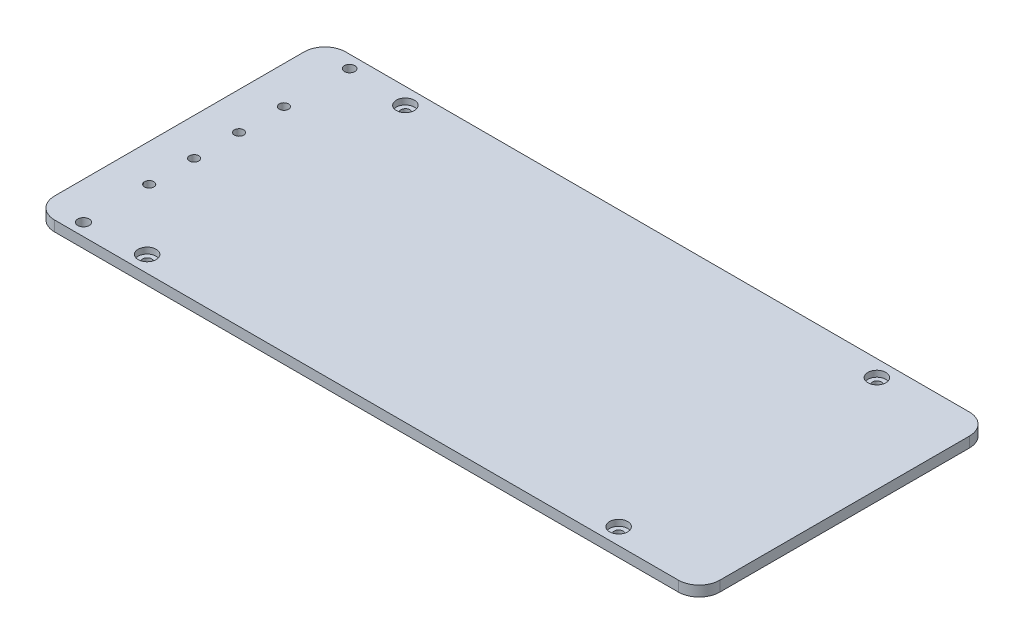
SolidWorks part; units mm, degrees
material "1060 Alloy"
ref_plane "Front Plane" through (0, 0, 0) normal (0, 0, 1) x (1, 0, 0)
ref_plane "Top Plane" through (0, 0, 0) normal (0, 1, 0) x (1, 0, 0)
ref_plane "Right Plane" through (0, 0, 0) normal (1, 0, 0) x (0, 0, -1)
sketch "Sketch1" plane through (0, 0, 0) normal (0, 1, 0) x (1, 0, 0)
  line L1 (-203.2, 88.9) -> (203.2, 88.9)
  line L2 (-203.2, 88.9) -> (-203.2, -88.9)
  line L3 (-203.2, -88.9) -> (203.2, -88.9)
  line L4 (203.2, 88.9) -> (203.2, -88.9)
  line L5 (-203.2, 88.9) -> (203.2, -88.9) construction
  line L6 (-203.2, -88.9) -> (203.2, 88.9) construction
  point P0 (0, 0)
  dimension "D1" = 406.4
  dimension "D2" = 177.8
extrude "Boss-Extrude1" add sketch "Sketch1" along normal blind 6.35 contours L4 L3 L2 L1
fillet "Fillet1" radius 12.7 4 edges at (-203.2, 3.175, -88.9) (-203.2, 3.175, 88.9) (203.2, 3.175, -88.9) (203.2, 3.175, 88.9)
sketch "Sketch2" plane through (0, 6.35, 0) normal (0, 1, 0) x (1, 0, 0)
  point P0 (-143.9998, -78.8646)
hole_wizard "CBORE for M5 Pan Head Machine Screw1" positions "Sketch2" profile "Sketch3" counterbore size "M5" standard "ANSI Metric" end condition through all
sketch "Sketch3" plane through (-143.9998, 6.35, 78.8646) normal (1, 0, 0) x (0, 0, 1)
  line L0 (0, 0) -> (0, 6.35)
  line L1 (0, 6.35) -> (2.75, 6.35)
  line L3 (2.75, 6.35) -> (2.75, 3.7)
  line L4 (2.75, 3.7) -> (5.5, 3.7)
  line L5 (5.5, 3.7) -> (5.5, 0)
  line L7 (5.5, 0) -> (0, 0)
  line L11 (0, -6.35) -> (0, 107.95) construction
  dimension "Thru Hole Dia." = 5.5
  dimension "Thru Hole Depth" = 6.35
  dimension "C'Bore Dia." = 11
  dimension "C'Bore Depth" = 3.7
mirror "Mirror1" about plane through (0, 0, 0) normal (1, 0, 0) of "CBORE for M5 Pan Head Machine Screw1"
mirror "Mirror2" about plane through (0, 0, 0) normal (0, 0, 1) of "Mirror1", "CBORE for M5 Pan Head Machine Screw1"
sketch "Sketch4" plane through (0, 6.35, 0) normal (0, 1, 0) x (1, 0, 0)
  circle A0 centre (-180.4458, 81.28) radius 3.175 construction
  circle A1 centre (-180.4458, -81.28) radius 3.4925 construction
  circle A2 centre (-180.4458, 81.28) radius 3.175
  circle A3 centre (-180.4458, -81.28) radius 3.4925
extrude "Cut-Extrude1" cut sketch "Sketch4" against normal through all
sketch "Sketch5" plane through (0, 6.35, 0) normal (0, 1, 0) x (1, 0, 0)
  circle A0 centre (-180.4458, 41.148) radius 2.8364
  circle A1 centre (-180.4458, 13.716) radius 2.8364
  circle A2 centre (-180.4458, -13.716) radius 2.8364
  circle A3 centre (-180.4458, -41.148) radius 2.8364
  dimension "D1" = 5.6728
  dimension "D2" = 5.6728
  dimension "D3" = 5.6728
  dimension "D4" = 5.6728
extrude "Cut-Extrude2" cut sketch "Sketch5" against normal through all
